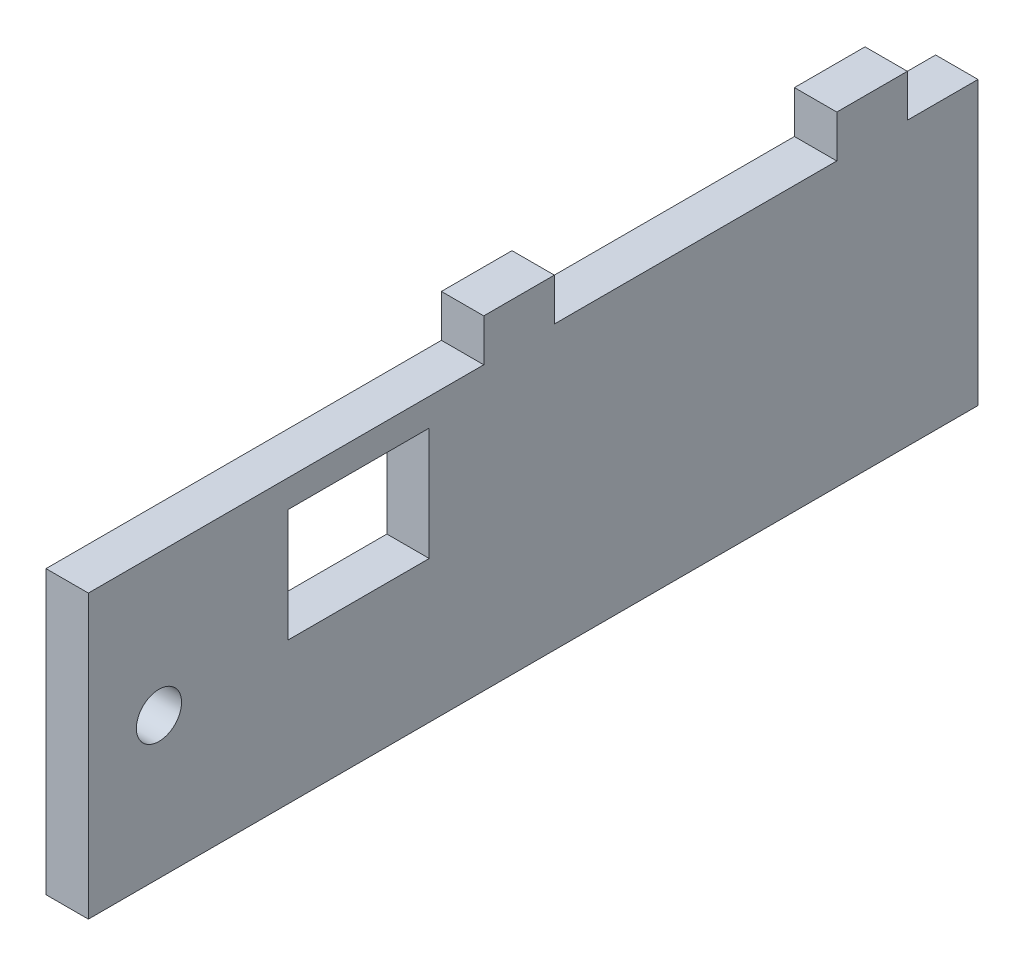
SolidWorks part; units mm, degrees
ref_plane "正面" through (0, 0, 0) normal (0, 0, 1) x (1, 0, 0)
ref_plane "平面" through (0, 0, 0) normal (0, 1, 0) x (1, 0, 0)
ref_plane "右側面" through (0, 0, 0) normal (1, 0, 0) x (0, 0, -1)
sketch "ｽｹｯﾁ1" plane through (0, 0, 0) normal (1, 0, 0) x (0, 0, -1)
  line L0 (17, 27) -> (17, 7)
  line L1 (45, 27) -> (45, 30)
  line L2 (45, 30) -> (50, 30)
  line L3 (50, 30) -> (50, 27)
  line L4 (17, 27) -> (45, 27)
  line L5 (80, 27) -> (80, 7)
  line L6 (17, 7) -> (80, 7)
  line L7 (70, 27) -> (70, 30)
  line L8 (70, 30) -> (75, 30)
  line L9 (75, 30) -> (75, 27)
  line L10 (75, 27) -> (80, 27)
  line L11 (50, 27) -> (70, 27)
  line L13 (41.14, 25.05) -> (31.14, 25.05)
  line L14 (41.14, 25.05) -> (41.14, 17.05)
  line L15 (41.14, 17.05) -> (31.14, 17.05)
  line L16 (31.14, 25.05) -> (31.14, 17.05)
  circle A0 centre (22, 17) radius 1.6
extrude "ﾎﾞｽ - 押し出し1" add sketch "ｽｹｯﾁ1" along normal blind 3
